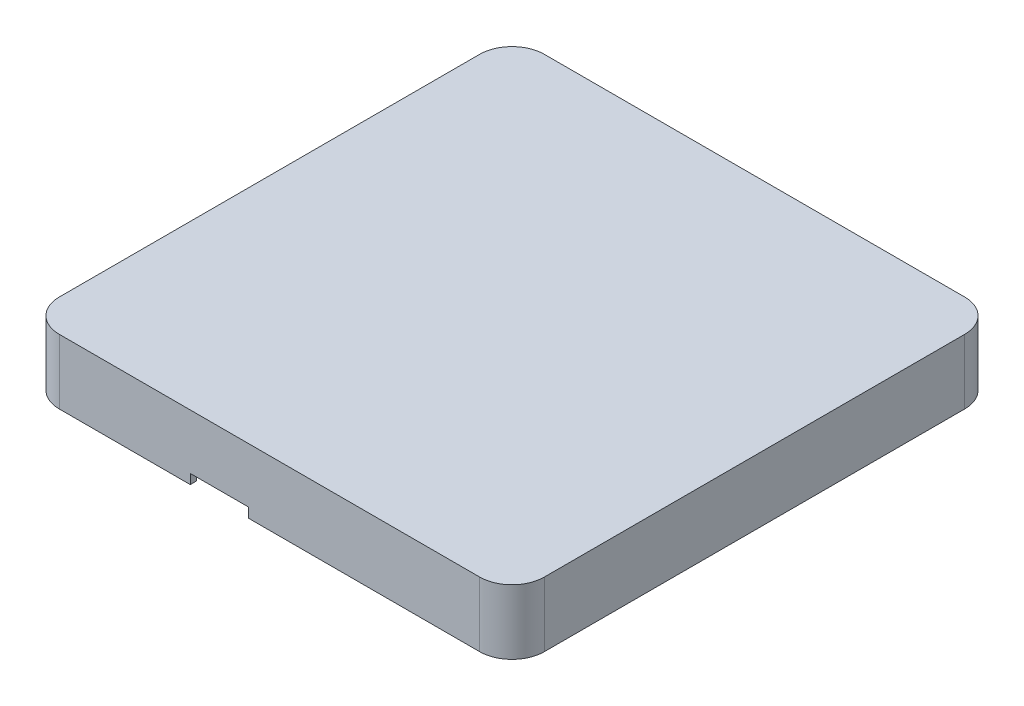
SolidWorks part; units mm, degrees
material "ABS"
ref_plane "Płaszczyzna przednia" through (0, 0, 0) normal (0, 0, 1) x (1, 0, 0)
ref_plane "Płaszczyzna górna" through (0, 0, 0) normal (0, 1, 0) x (1, 0, 0)
ref_plane "Płaszczyzna prawa" through (0, 0, 0) normal (1, 0, 0) x (0, 0, -1)
sketch "Szkic1" plane through (0, 0, 0) normal (0, 1, 0) x (1, 0, 0)
  line L0 (0, 0) -> (0, 75)
  line L1 (0, 75) -> (75, 75)
  line L2 (75, 75) -> (75, 0)
  line L3 (75, 0) -> (0, 0)
  dimension "D1" = 75
  dimension "D2" = 75
extrude "Dodanie-wyciągnięcie1" add sketch "Szkic1" along normal blind 10
fillet "Zaokrąglenie1" radius 5 4 edges at (0, 5, 0) (0, 5, -75) (75, 5, -75) (75, 5, 0)
sketch "Szkic4" plane through (0, 10, 0) normal (0, 1, 0) x (1, 0, 0)
  line L8 (2, 70) -> (2, 5)
  line L9 (5, 2) -> (70, 2)
  line L10 (73, 5) -> (73, 70)
  line L11 (70, 73) -> (5, 73)
  line L12 (2, 70) -> (2, 5)
  line L13 (5, 2) -> (70, 2)
  line L14 (73, 5) -> (73, 70)
  line L15 (70, 73) -> (5, 73)
  arc A8 (2, 5) -> (5, 2) centre (5, 5) ccw
  arc A9 (70, 2) -> (73, 5) centre (70, 5) ccw
  arc A10 (73, 70) -> (70, 73) centre (70, 70) ccw
  arc A11 (5, 73) -> (2, 70) centre (5, 70) ccw
  arc A12 (2, 5) -> (5, 2) centre (5, 5) ccw
  arc A13 (70, 2) -> (73, 5) centre (70, 5) ccw
  arc A14 (73, 70) -> (70, 73) centre (70, 70) ccw
  arc A15 (5, 73) -> (2, 70) centre (5, 70) ccw
  dimension "D1" = 2
extrude "Wytnij-wyciągnięcie1" cut sketch "Szkic4" against normal blind 8
sketch "Szkic6" plane through (0, 10, 0) normal (0, 1, 0) x (1, 0, 0)
  line L0 (2, 70) -> (2, 5)
  line L1 (5, 2) -> (70, 2)
  line L2 (73, 5) -> (73, 70)
  line L3 (70, 73) -> (5, 73)
  line L8 (1, 70) -> (1, 5)
  line L9 (5, 1) -> (70, 1)
  line L10 (74, 5) -> (74, 70)
  line L11 (70, 74) -> (5, 74)
  line L12 (1, 70) -> (1, 5)
  line L13 (5, 1) -> (70, 1)
  line L14 (74, 5) -> (74, 70)
  line L15 (70, 74) -> (5, 74)
  arc A0 (2, 5) -> (5, 2) centre (5, 5) ccw
  arc A1 (70, 2) -> (73, 5) centre (70, 5) ccw
  arc A2 (73, 70) -> (70, 73) centre (70, 70) ccw
  arc A3 (5, 73) -> (2, 70) centre (5, 70) ccw
  arc A8 (1, 5) -> (5, 1) centre (5, 5) ccw
  arc A9 (70, 1) -> (74, 5) centre (70, 5) ccw
  arc A10 (74, 70) -> (70, 74) centre (70, 70) ccw
  arc A11 (5, 74) -> (1, 70) centre (5, 70) ccw
  arc A12 (1, 5) -> (5, 1) centre (5, 5) ccw
  arc A13 (70, 1) -> (74, 5) centre (70, 5) ccw
  arc A14 (74, 70) -> (70, 74) centre (70, 70) ccw
  arc A15 (5, 74) -> (1, 70) centre (5, 70) ccw
  dimension "D1" = 1
  dimension "D2" = 1
extrude "Wytnij-wyciągnięcie2" cut sketch "Szkic6" against normal blind 4
sketch "Szkic7" plane through (0, 2, 0) normal (0, 1, 0) x (1, 0, 0)
  line L0 (2, 70) -> (2, 5) construction
  line L1 (5, 0) -> (70, 0) construction
  line L2 (5, 2) -> (70, 2) construction
  line L5 (2, 70) -> (2, 5) construction
  circle A0 centre (24, 52) radius 0.9
  circle A1 centre (35.5, 52) radius 0.9005
  circle A2 centre (24, 5) radius 0.9
  circle A3 centre (35.5, 5) radius 0.9
  circle A4 centre (24, 52) radius 1.9
  circle A5 centre (35.5, 52) radius 1.9005
  circle A6 centre (35.5, 5) radius 1.9
  circle A7 centre (24, 5) radius 1.9
  point P22 (0, 0)
  dimension "D1" = 22
  dimension "D3" = 1.8
  dimension "D5" = 1.801
  dimension "D7" = 1.8
  dimension "D10" = 11.5
  dimension "D11" = 1.8
  dimension "D2" = 5
  dimension "D4" = 11.5
  dimension "D6" = 3
  dimension "D8" = 47
  dimension "D9" = 22
  dimension "D12" = 47
  dimension "D13" = 1
extrude "Dodanie-wyciągnięcie2" add sketch "Szkic7" along normal blind 8.7
sketch "Szkic9" plane through (0, 2, 0) normal (0, 1, 0) x (1, 0, 0)
  line L4 (2, 70) -> (2, 5)
  line L5 (5, 2) -> (70, 2)
  line L6 (73, 5) -> (73, 70)
  line L7 (70, 73) -> (5, 73)
  line L8 (2, 70) -> (2, 5)
  line L9 (5, 2) -> (70, 2)
  line L10 (73, 5) -> (73, 70)
  line L11 (70, 73) -> (5, 73)
  circle A0 centre (35.5, 52) radius 0.9005 construction
  circle A1 centre (35.5, 52) radius 0.9005
  circle A2 centre (35.5, 5) radius 0.9 construction
  circle A3 centre (24, 5) radius 0.9 construction
  arc A4 (5, 73) -> (2, 70) centre (5, 70) ccw
  arc A5 (2, 5) -> (5, 2) centre (5, 5) ccw
  arc A6 (70, 2) -> (73, 5) centre (70, 5) ccw
  arc A7 (73, 70) -> (70, 73) centre (70, 70) ccw
  arc A8 (5, 73) -> (2, 70) centre (5, 70) ccw
  arc A9 (2, 5) -> (5, 2) centre (5, 5) ccw
  arc A10 (70, 2) -> (73, 5) centre (70, 5) ccw
  arc A11 (73, 70) -> (70, 73) centre (70, 70) ccw
  circle A12 centre (24, 52) radius 0.9 construction
  circle A13 centre (35.5, 5) radius 0.9
  circle A14 centre (24, 5) radius 0.9
  circle A15 centre (24, 52) radius 0.9
  dimension "D1" = 0
extrude "Dodanie-wyciągnięcie3" add sketch "Szkic9" along normal blind 1 contours A15 | A1 | A14 | A13
sketch "Szkic10" plane through (0, 2, 0) normal (0, 1, 0) x (1, 0, 0)
  line L0 (73, 5) -> (73, 70) construction
  line L1 (5, 2) -> (70, 2) construction
  circle A0 centre (67, 23.5) radius 1.25
  circle A1 centre (67, 8) radius 1.25
  dimension "D1" = 2.5
  dimension "D2" = 2.5
  dimension "D4" = 6
  dimension "D3" = 15.5
  dimension "D5" = 6
  dimension "D6" = 21.5
extrude "Dodanie-wyciągnięcie4" add sketch "Szkic10" along normal blind 1
sketch "Szkic11" plane through (0, 2, 0) normal (0, 1, 0) x (1, 0, 0)
  line L4 (2, 70) -> (2, 5)
  line L5 (5, 2) -> (70, 2)
  line L6 (73, 5) -> (73, 70)
  line L7 (70, 73) -> (5, 73)
  line L8 (2, 70) -> (2, 5)
  line L9 (5, 2) -> (70, 2)
  line L10 (73, 5) -> (73, 70)
  line L11 (70, 73) -> (5, 73)
  circle A0 centre (67, 8) radius 1.25 construction
  circle A1 centre (67, 23.5) radius 1.25 construction
  circle A2 centre (67, 8) radius 1.25
  circle A3 centre (67, 23.5) radius 1.25
  arc A4 (5, 73) -> (2, 70) centre (5, 70) ccw
  arc A5 (2, 5) -> (5, 2) centre (5, 5) ccw
  arc A6 (70, 2) -> (73, 5) centre (70, 5) ccw
  arc A7 (73, 70) -> (70, 73) centre (70, 70) ccw
  arc A8 (5, 73) -> (2, 70) centre (5, 70) ccw
  arc A9 (2, 5) -> (5, 2) centre (5, 5) ccw
  arc A10 (70, 2) -> (73, 5) centre (70, 5) ccw
  arc A11 (73, 70) -> (70, 73) centre (70, 70) ccw
  circle A12 centre (67, 23.5) radius 2
  circle A13 centre (67, 8) radius 2
  circle M9 centre (67, 8) radius 1.25
  circle M10 centre (67, 23.5) radius 1.25
  dimension "D1" = 0
  dimension "D2" = 0.75
extrude "Dodanie-wyciągnięcie5" add sketch "Szkic11" along normal blind 8.5 contours A12 M10 | A13 M9
ref_plane "Płaszczyzna1" through (0, -10, 0) normal (0, 1, 0) x (1, 0, 0)
sketch "Szkic19" plane through (0, 0, -2) normal (0, 0, -1) x (-1, 0, 0)
  line L0 (-29.75, 10) -> (-29.75, 2) construction
  line L1 (-5, 2) -> (-70, 2) construction
  line L2 (-5, 2) -> (-5, 6) construction
  line L3 (-2, 2) -> (-2, 6) construction
  line L4 (-5, 10) -> (-70, 10) construction
  line L10 (-34.25, 10) -> (-25.25, 10)
  line L12 (-5, 10) -> (-70, 10) construction
  line L13 (-32.5, 8.5) -> (-26.5, 8.5)
  line L14 (-34.25, 10) -> (-34.25, 8.5)
  line L15 (-34.25, 8.5) -> (-32.5, 8.5)
  line L16 (-25.25, 10) -> (-25.25, 8.5)
  line L17 (-25.25, 8.5) -> (-26.5, 8.5)
  dimension "D2" = 9
  dimension "D1" = 27.75
  dimension "D5" = 1.5
  dimension "D6" = 4.5
extrude "Wytnij-wyciągnięcie20" cut sketch "Szkic19" against normal blind 10
sketch "Szkic22" plane through (74, 0, 0) normal (-1, 0, 0) x (0, 0, 1)
  line L0 (-39.5, 9) -> (-35.5, 9)
  line L1 (-65, 9) -> (-61, 9)
  line L2 (-65, 9) -> (-65, 10)
  line L3 (-65, 10) -> (-61, 10)
  line L4 (-61, 9) -> (-61, 10)
  line L5 (-75, 10) -> (-75, 0) construction
  line L6 (-14, 9) -> (-14, 10)
  line L7 (-14, 10) -> (-10, 10)
  line L8 (-10, 9) -> (-10, 10)
  line L9 (-14, 9) -> (-10, 9)
  line L10 (0, 0) -> (0, 10) construction
  line L11 (-5, 10) -> (-70, 10) construction
  line L12 (-39.5, 9) -> (-39.5, 10)
  line L13 (-39.5, 10) -> (-35.5, 10)
  line L14 (-35.5, 9) -> (-35.5, 10)
  point P14 (-63, 9)
  point P19 (-37.5, 9)
  dimension "D1" = 4
  dimension "D2" = 1
  dimension "D3" = 10
  dimension "D5" = 10
  dimension "D7" = 25.5
  dimension "D4" = 2
  dimension "D6" = 2
extrude "Dodanie-wyciągnięcie6" add sketch "Szkic22" along normal blind 0.3
ref_plane "Płaszczyzna2" through (1, 10, -5) normal (0, 0, 1) x (1, 0, 0)
sketch "Szkic24" plane through (1, 0, 0) normal (1, 0, 0) x (0, 0, -1)
  line L0 (70, 10) -> (5, 10) construction
  line L1 (10, 10) -> (14, 10)
  line L2 (10, 10) -> (10, 9)
  line L3 (10, 9) -> (14, 9)
  line L4 (14, 10) -> (14, 9)
  line L5 (0, 10) -> (0, 0) construction
  line L6 (61, 10) -> (65, 10)
  line L7 (61, 9) -> (65, 9)
  line L8 (61, 10) -> (61, 9)
  line L9 (65, 10) -> (65, 9)
  line L10 (75, 0) -> (75, 10) construction
  line L11 (35.5, 10) -> (35.5, 9)
  line L12 (35.5, 10) -> (39.5, 10)
  line L13 (35.5, 9) -> (39.5, 9)
  line L14 (39.5, 10) -> (39.5, 9)
  point P15 (12, 9)
  point P19 (37.5, 9)
  dimension "D1" = 4
  dimension "D2" = 1
  dimension "D3" = 10
  dimension "D5" = 10
  dimension "D7" = 25.5
  dimension "D4" = 2
  dimension "D6" = 2
extrude "Dodanie-wyciągnięcie7" add sketch "Szkic24" along normal blind 0.3
sketch "Szkic25" plane through (0, 0, -10) normal (0, 0, 1) x (1, 0, 0)
  line L0 (1, 10) -> (1.3, 9.5)
  line L1 (1.3, 10) -> (1.3, 9) construction
  line L2 (1, 10) -> (1.3, 10)
  line L3 (1.3, 10) -> (1.3, 9.5)
extrude "Wytnij-wyciągnięcie13" cut sketch "Szkic25" against normal blind 55
sketch "Szkic26" plane through (0, 0, -65) normal (0, 0, -1) x (-1, 0, 0)
  line L0 (-74, 10) -> (-73.7, 10)
  line L1 (-73.7, 10) -> (-73.7, 9.5)
  line L2 (-73.7, 10) -> (-73.7, 9) construction
  line L3 (-73.7, 9.5) -> (-74, 10)
extrude "Wytnij-wyciągnięcie14" cut sketch "Szkic26" against normal blind 55
ref_plane "Płaszczyzna3" through (1, 10, -54) normal (0, 0, 1) x (1, 0, 0)
ref_plane "Płaszczyzna4" through (0, 0, -25) normal (0, 0, -1) x (-1, 0, 0)
mirror "Lustro5" about plane through (0, -10, 0) normal (0, 1, 0) of bodies 133 137
delete or keep bodies "Obiekt-Usuń/zachowaj 1" type delete bodies bodies 133
